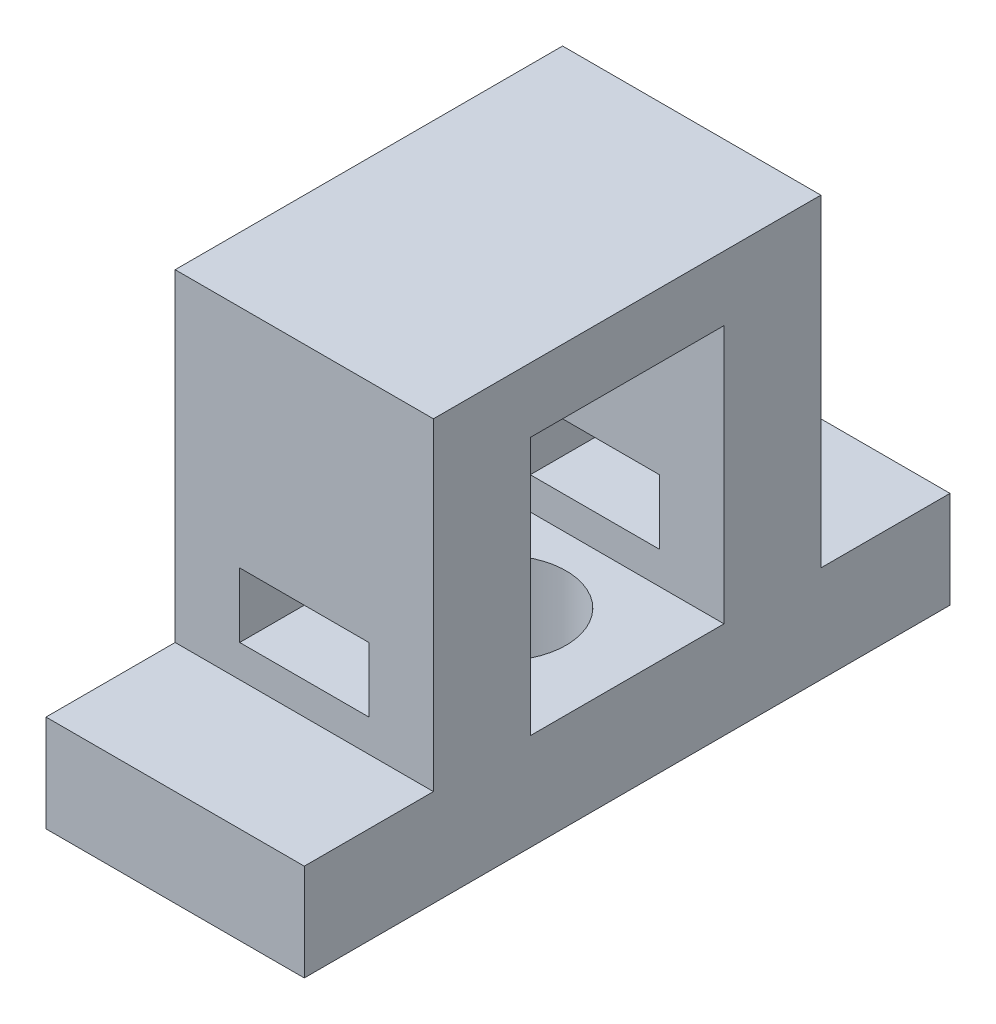
SolidWorks part; units mm, degrees
ref_plane "Front Plane" through (0, 0, 0) normal (0, 0, 1) x (1, 0, 0)
ref_plane "Top Plane" through (0, 0, 0) normal (0, 1, 0) x (1, 0, 0)
ref_plane "Right Plane" through (0, 0, 0) normal (1, 0, 0) x (0, 0, -1)
sketch "Sketch1" plane through (0, 0, 0) normal (1, 0, 0) x (0, 0, -1)
  line L0 (-12.0895, -57.04) -> (-12.0895, -42.04)
  line L1 (-12.0895, -42.04) -> (7.9105, -42.04)
  line L2 (7.9105, -42.04) -> (7.9105, 7.96)
  line L3 (7.9105, 7.96) -> (67.9105, 7.96)
  line L4 (67.9105, 7.96) -> (67.9105, -42.04)
  line L5 (67.9105, -42.04) -> (87.9105, -42.04)
  line L6 (87.9105, -42.04) -> (87.9105, -57.04)
  line L7 (87.9105, -57.04) -> (-12.0895, -57.04)
  line L17 (22.9105, -2.04) -> (52.9105, -2.04)
  line L18 (22.9105, -2.04) -> (22.9105, -42.04)
  line L19 (22.9105, -42.04) -> (52.9105, -42.04)
  line L20 (52.9105, -2.04) -> (52.9105, -42.04)
  line L21 (22.9105, -2.04) -> (52.9105, -42.04) construction
  line L22 (22.9105, -42.04) -> (52.9105, -2.04) construction
  point P2 (37.9105, -22.04)
  point P13 (37.9105, -2.04)
  dimension "D1" = 40
  dimension "D2" = 50
  dimension "D3" = 15
  dimension "D4" = 15
  dimension "D5" = 30
  dimension "D6" = 15
  dimension "D7" = 100
  dimension "D8" = 15
  dimension "D9" = 10
extrude "Boss-Extrude1" add sketch "Sketch1" along normal blind 40
sketch "Sketch2" plane through (0, 0, -7.9105) normal (0, 0, 1) x (1, 0, 0)
  line L0 (40, -42.04) -> (0, -42.04) construction
  line L1 (10, -37.04) -> (30, -37.04)
  line L2 (10, -37.04) -> (10, -27.04)
  line L3 (10, -27.04) -> (30, -27.04)
  line L4 (30, -37.04) -> (30, -27.04)
  line L5 (10, -37.04) -> (30, -27.04) construction
  line L6 (10, -27.04) -> (30, -37.04) construction
  line L7 (40, 7.96) -> (40, -42.04) construction
  point P0 (20, -32.04)
  dimension "D1" = 10
  dimension "D2" = 20
  dimension "D3" = 15
  dimension "D4" = 10
extrude "Cut-Extrude1" cut sketch "Sketch2" against normal through all
ref_plane "Plane1" through (0, -42.04, 0) normal (0, 1, 0) x (1, 0, 0)
sketch "Sketch3" plane through (0, -42.04, 0) normal (0, 1, 0) x (1, 0, 0)
  circle A1 centre (20.6522, 37.8018) radius 10
  dimension "D1" = 20
extrude "Cut-Extrude2" cut sketch "Sketch3" against normal through all
